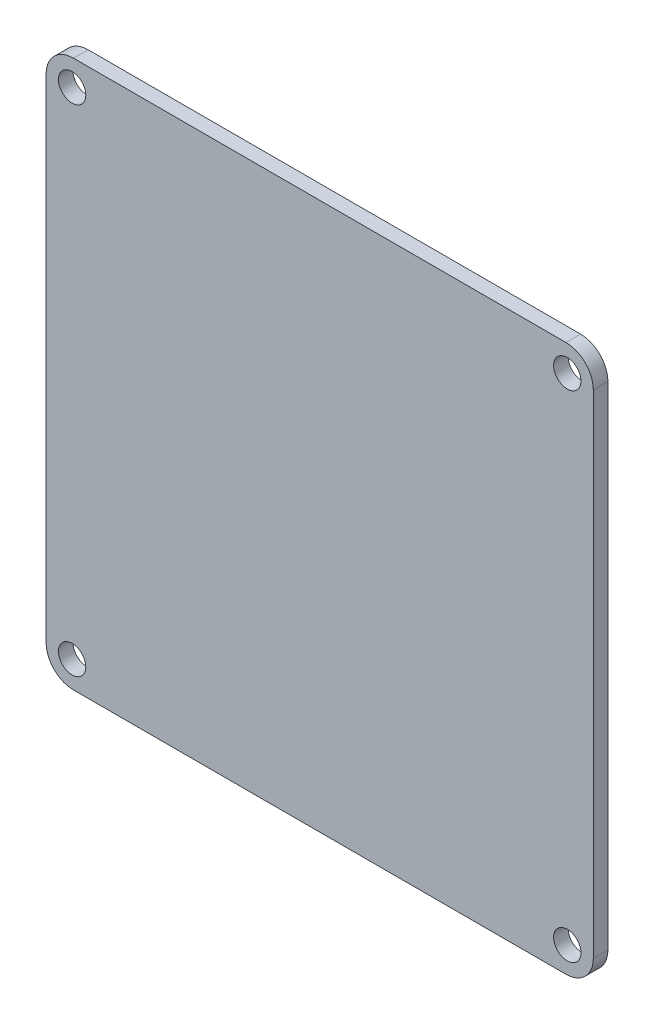
SolidWorks part; units mm, degrees
ref_plane "前视基准面" through (0, 0, 0) normal (0, 0, 1) x (1, 0, 0)
ref_plane "上视基准面" through (0, 0, 0) normal (0, 1, 0) x (1, 0, 0)
ref_plane "右视基准面" through (0, 0, 0) normal (1, 0, 0) x (0, 0, -1)
sketch "草图1" plane through (0, 0, 0) normal (0, 0, 1) x (1, 0, 0)
  line L1 (0, 0) -> (60, 0)
  line L2 (0, 0) -> (0, -60)
  line L3 (0, -60) -> (60, -60)
  line L4 (60, 0) -> (60, -60)
extrude "凸台-拉伸2" add sketch "草图1" along normal blind 1.6
sketch "草图3" plane through (0, 0, 0) normal (0, 0, -1) x (-1, 0, 0)
  circle A0 centre (-57.15, -2.85) radius 1.5
  circle A1 centre (-2.85, -2.85) radius 1.5
  circle A2 centre (-2.85, -57.15) radius 1.5
  circle A3 centre (-57.15, -57.15) radius 1.5
extrude "切除-拉伸1" cut sketch "草图3" against normal blind 19.6
fillet "圆角1" radius 3 1 edges at (60, 0, 0.8)
fillet "圆角2" radius 3 1 edges at (0, 0, 0.8)
fillet "圆角3" radius 3 1 edges at (0, -60, 0.8)
fillet "圆角4" radius 3 1 edges at (60, -60, 0.8)
